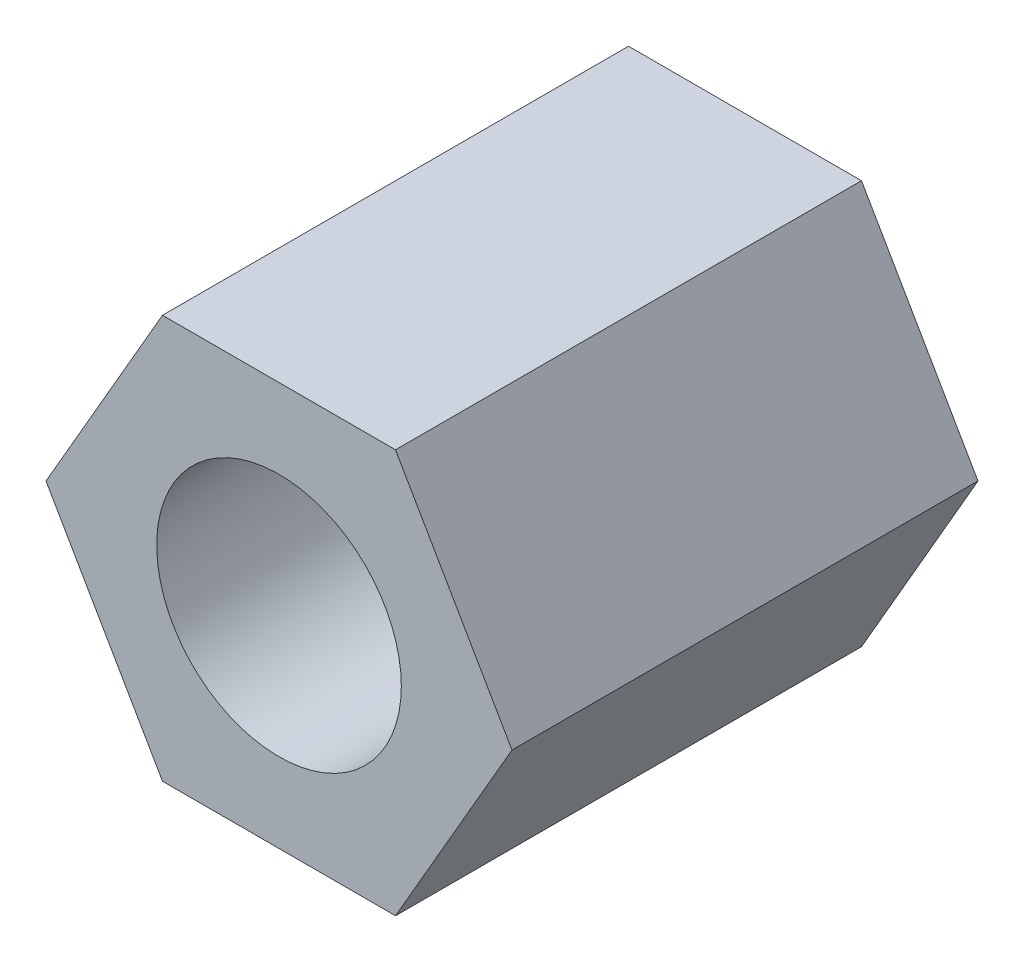
SolidWorks part; units mm, degrees
material "普通碳钢"
ref_plane "前视" through (0, 0, 0) normal (0, 0, 1) x (1, 0, 0)
ref_plane "上视" through (0, 0, 0) normal (0, 1, 0) x (1, 0, 0)
ref_plane "右视" through (0, 0, 0) normal (1, 0, 0) x (0, 0, -1)
sketch "草图1" plane through (0, 0, 0) normal (0, 0, 1) x (1, 0, 0)
  line L0 (0, 0) -> (4, 0)
  line L1 (4, 0) -> (6, -3.4641)
  line L2 (6, -3.4641) -> (4, -6.9282)
  line L3 (4, -6.9282) -> (0, -6.9282)
  line L4 (0, -6.9282) -> (-2, -3.4641)
  line L5 (-2, -3.4641) -> (0, 0)
  dimension "D1" = 8
  dimension "D2" = 8
extrude "凸台-拉伸1" add sketch "草图1" along normal blind 8
hole_wizard "M5" positions "草图3" profile "草图2" tap size "M5" standard "GB" end condition through all
sketch "草图3" plane through (0, 0, 8) normal (0, 0, 1) x (1, 0, 0)
  line L0 (-2, -3.4641) -> (6, -3.4641) construction
  line L2 (2, 0) -> (2, -6.9282) construction
  line L3 (4, 0) -> (0, 0) construction
  line L4 (0, -6.9282) -> (4, -6.9282) construction
  point P0 (2, -3.4641)
cosmetic thread "孔螺蚊线1"
sketch "草图2" plane through (2, -3.4641, 8) normal (1, 0, 0) x (0, -1, 0)
  line L0 (0, 0) -> (0, 8)
  line L1 (0, 8) -> (2.1, 8)
  line L2 (2.1, 8) -> (2.1, 0)
  line L5 (2.1, 0) -> (0, 0)
  line L11 (0, -6.35) -> (0, 107.95) construction
  dimension "通孔螺纹孔钻头直径" = 4.2
  dimension "通孔螺纹孔钻头深度" = 8
